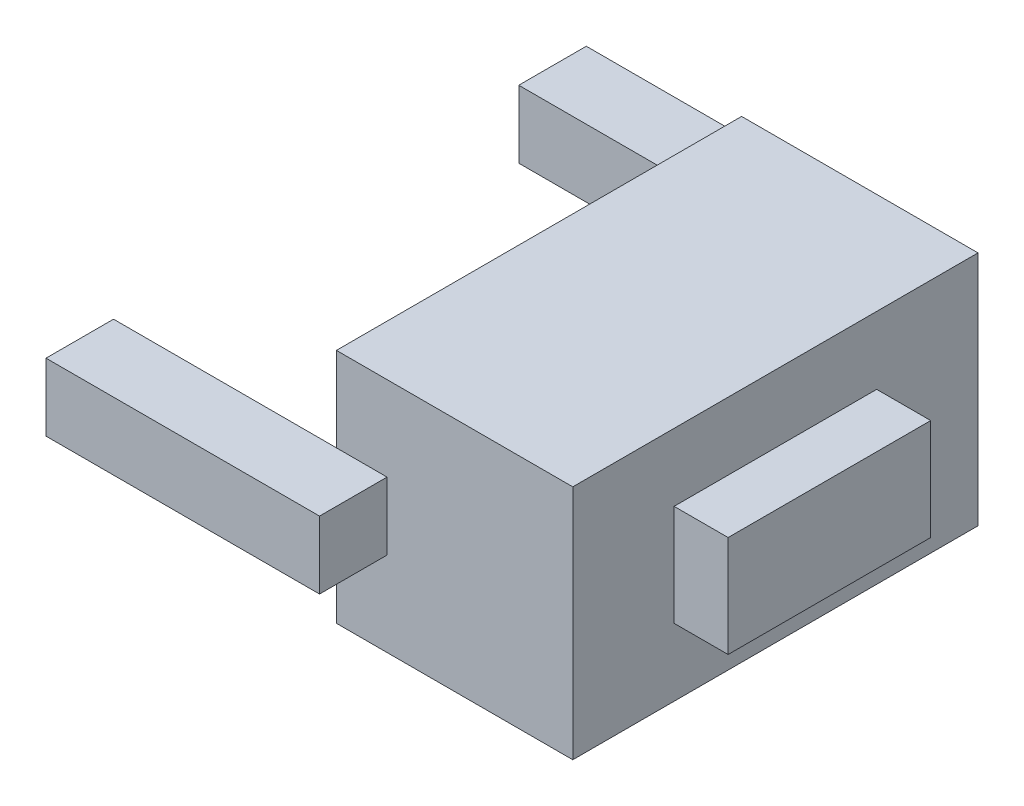
SolidWorks part; units mm, degrees
ref_plane "Front Plane" through (0, 0, 0) normal (0, 0, 1) x (1, 0, 0)
ref_plane "Top Plane" through (0, 0, 0) normal (0, 1, 0) x (1, 0, 0)
ref_plane "Right Plane" through (0, 0, 0) normal (1, 0, 0) x (0, 0, -1)
sketch "Sketch1" plane through (0, 0, 0) normal (1, 0, 0) x (0, 0, -1)
  line L1 (0, 0) -> (6, 0)
  line L2 (0, 0) -> (0, 3.5)
  line L3 (0, 3.5) -> (6, 3.5)
  line L4 (6, 0) -> (6, 3.5)
  dimension "D1" = 6
  dimension "D2" = 3.5
extrude "Boss-Extrude1" add sketch "Sketch1" along normal blind 3.5
sketch "Sketch2" plane through (3.5, 0, 0) normal (1, 0, 0) x (0, 0, -1)
  line L0 (0, 3.5) -> (0, 0) construction
  line L1 (1.5, 1) -> (4.5, 1)
  line L2 (1.5, 1) -> (1.5, 2.5)
  line L3 (1.5, 2.5) -> (4.5, 2.5)
  line L4 (4.5, 1) -> (4.5, 2.5)
  line L5 (0, 0) -> (6, 0) construction
  dimension "D1" = 3
  dimension "D2" = 1.5
  dimension "D3" = 1.5
  dimension "D4" = 1
extrude "Boss-Extrude2" add sketch "Sketch2" along normal blind 0.8
sketch "Sketch7" plane through (0, 0, 0) normal (0, 0, 1) x (1, 0, 0)
  line L0 (0, 3.5) -> (0, 0) construction
  line L1 (0, 2.25) -> (0.75, 2.25)
  line L2 (0, 2.25) -> (0, 1.25)
  line L3 (0, 1.25) -> (0.75, 1.25)
  line L4 (0.75, 2.25) -> (0.75, 1.25)
  line L5 (3.5, 3.5) -> (0, 3.5) construction
  dimension "D1" = 1
  dimension "D2" = 0.75
  dimension "D3" = 1.25
extrude "Boss-Extrude7" add sketch "Sketch7" along normal blind 1
sketch "Sketch8" plane through (0, 0, 0) normal (-1, 0, 0) x (0, 0, 1)
  line L1 (0, 2.25) -> (1, 2.25)
  line L2 (0, 2.25) -> (0, 1.25)
  line L3 (0, 1.25) -> (1, 1.25)
  line L4 (1, 2.25) -> (1, 1.25)
extrude "Boss-Extrude8" add sketch "Sketch8" along normal blind 3.3
sketch "Sketch9" plane through (0, 0, -6) normal (0, 0, -1) x (-1, 0, 0)
  line L0 (0, 0) -> (0, 3.5) construction
  line L1 (0, 2.25) -> (-0.75, 2.25)
  line L2 (0, 2.25) -> (0, 1.25)
  line L3 (0, 1.25) -> (-0.75, 1.25)
  line L4 (-0.75, 2.25) -> (-0.75, 1.25)
  line L5 (-3.5, 3.5) -> (0, 3.5) construction
  dimension "D1" = 1
  dimension "D2" = 0.75
  dimension "D3" = 1.25
extrude "Boss-Extrude9" add sketch "Sketch9" along normal blind 1
sketch "Sketch10" plane through (0, 0, 0) normal (-1, 0, 0) x (0, 0, 1)
  line L1 (-7, 2.25) -> (-6, 2.25)
  line L2 (-7, 2.25) -> (-7, 1.25)
  line L3 (-7, 1.25) -> (-6, 1.25)
  line L4 (-6, 2.25) -> (-6, 1.25)
extrude "Boss-Extrude10" add sketch "Sketch10" along normal blind 3.3
